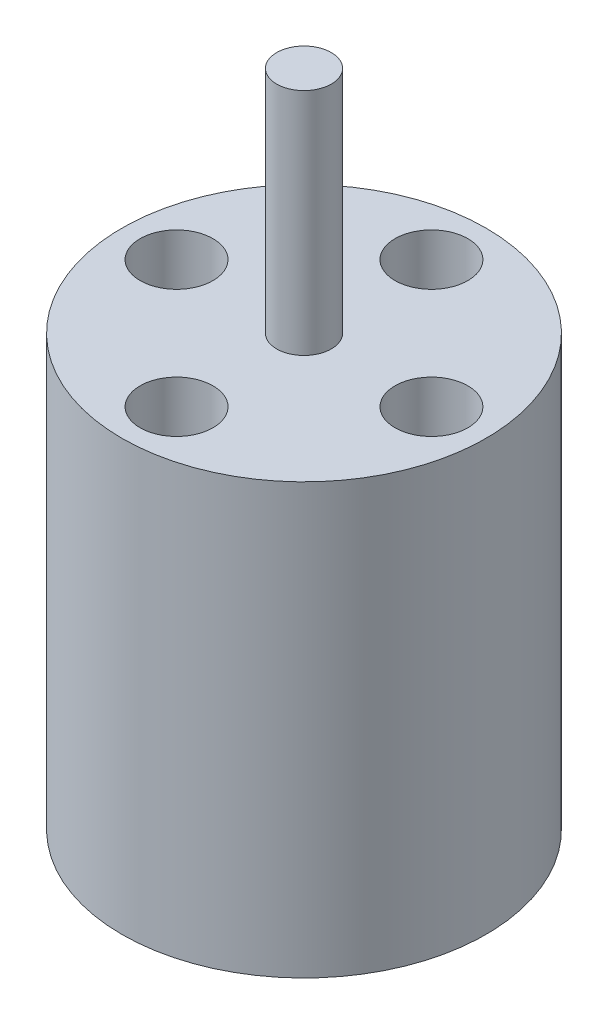
SolidWorks part; units mm, degrees
ref_plane "前视基准面" through (0, 0, 0) normal (0, 0, 1) x (1, 0, 0)
ref_plane "上视基准面" through (0, 0, 0) normal (0, 1, 0) x (1, 0, 0)
ref_plane "右视基准面" through (0, 0, 0) normal (1, 0, 0) x (0, 0, -1)
other "Configuration Table"
sketch "草图1" plane through (0, 0, 0) normal (0, 1, 0) x (1, 0, 0)
  circle A0 centre (-0.143, 0) radius 5
  dimension "D1" = 10
extrude "凸台-拉伸1" add sketch "草图1" along normal blind 11.8
sketch "草图2" plane through (0, 11.8, 0) normal (0, 1, 0) x (1, 0, 0)
  line L0 (-5.143, 0) -> (4.857, 0) construction
  circle A0 centre (-0.143, 0) radius 0.75
  circle A1 centre (4.857, 0) radius 1
  circle A2 centre (-0.143, -5) radius 1
  circle A3 centre (-5.143, 0) radius 1
  circle A4 centre (-0.143, 5) radius 1
  circle A5 centre (-0.143, 0) radius 5 construction
  dimension "D1" = 1.5
  dimension "D2" = 2
  dimension "D4" = 5
  dimension "D3" = 4
extrude "凸台-拉伸3" add sketch "草图2" along normal blind 6.3 contours A0
sketch "草图4" plane through (0, 11.8, 0) normal (0, 1, 0) x (1, 0, 0)
  line L0 (-5.143, 0) -> (4.857, 0) construction
  line L1 (3.357, 0) -> (-3.643, 0) construction
  line L3 (-0.143, -3.5) -> (-0.143, 3.5) construction
  circle A3 centre (-0.143, -3.5) radius 1
  circle A4 centre (-0.143, 0) radius 5 construction
  circle A5 centre (-3.643, 0) radius 1
  circle A6 centre (-0.143, 3.5) radius 1
  circle A7 centre (3.357, 0) radius 1
  point P0 (-0.143, 0)
  dimension "D1" = 4
  dimension "D3" = 2
  dimension "D2" = 7
extrude "切除-拉伸1" cut sketch "草图4" against normal blind 5
